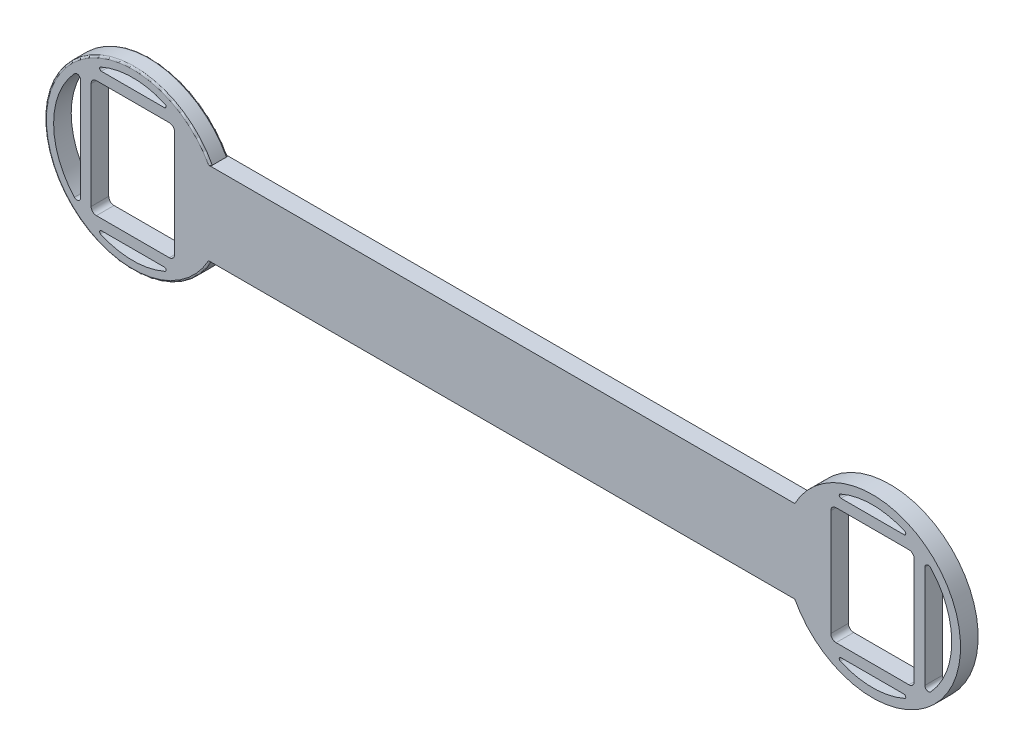
SolidWorks part; units mm, degrees
ref_plane "前视基准面" through (0, 0, 0) normal (0, 0, 1) x (1, 0, 0)
ref_plane "上视基准面" through (0, 0, 0) normal (0, 1, 0) x (1, 0, 0)
ref_plane "右视基准面" through (0, 0, 0) normal (1, 0, 0) x (0, 0, -1)
sketch "草图1" plane through (0, 0, 0) normal (0, 0, 1) x (1, 0, 0)
  line L0 (0, -114.9603) -> (0, 164.1005) construction
  line L1 (-210, -23.5) -> (0, -23.5)
  line L2 (-210, 23.5) -> (0, 23.5)
  line L3 (-210, 0) -> (-210, 65.4164) construction
  line L4 (-210, 0) -> (-106.141, 0) construction
  line L5 (-233.7, -33.2) -> (-233.7, 33.2)
  line L6 (-233.7, 33.2) -> (-186.3, 33.2)
  line L7 (-186.3, -33.2) -> (-186.3, 33.2)
  line L8 (-233.7, -33.2) -> (-186.3, -33.2)
  line L9 (-239.7, 0) -> (-239.7, 50.4262) construction
  line L10 (-239.7, 33.807) -> (-239.7, -33.807)
  line L11 (-180.3, 33.807) -> (-180.3, -33.807)
  line L12 (-210, 39.2) -> (-130.0604, 39.2) construction
  line L13 (-232.0989, 39.2) -> (-187.9011, 39.2)
  line L14 (-232.0989, -39.2) -> (-187.9011, -39.2)
  line L15 (0, 23.5) -> (0, -23.5)
  circle A0 centre (-210, 0) radius 23.5
  circle A1 centre (-210, 0) radius 50
  arc A2 (-239.7, -33.807) -> (-239.7, 33.807) centre (-210, 0) cw
  arc A3 (-180.3, -33.807) -> (-180.3, 33.807) centre (-210, 0) ccw
  arc A4 (-232.0989, 39.2) -> (-187.9011, 39.2) centre (-210, 0) cw
  arc A5 (-232.0989, -39.2) -> (-187.9011, -39.2) centre (-210, 0) ccw
  point P17 (-210, 33.2)
  point P19 (-186.3, 0)
  point P20 (-233.7, 0)
  dimension "D2" = 47
  dimension "D5" = 6
  dimension "D6" = 6
  dimension "D1" = 210
  dimension "D3" = 33.2
  dimension "D4" = 23.7
extrude "凸台-拉伸1" add sketch "草图1" along normal blind 10 contours A1 L1 L15 L2 | A3 L1 A1 L2 | A3 L2 A1 L1 L11 L7 L8 L5 L6 A5 L14 L10 A2 L13 A4 | L11 L2 L7 L1
fillet "圆角1" radius 3 4 edges at (-233.7, -33.2, 5) (-186.3, -33.2, 5) (-186.3, 33.2, 5) (-233.7, 33.2, 5)
fillet "圆角2" radius 2 2 edges at (-239.7, 33.807, 5) (-239.7, -33.807, 5)
fillet "圆角3" [suppressed] radius 2
fillet "圆角4" radius 1 4 edges at (-232.0989, -39.2, 5) (-187.9011, -39.2, 5) (-187.9011, 39.2, 5) (-232.0989, 39.2, 5)
fillet "圆角5" radius 1 2 edges at (-260, 0, 0) (-260, 0, 10)
mirror "镜向1" about plane through (0, 0, 10) normal (1, 0, 0) of "圆角2", "圆角3", "圆角1", "圆角4", "凸台-拉伸1"
